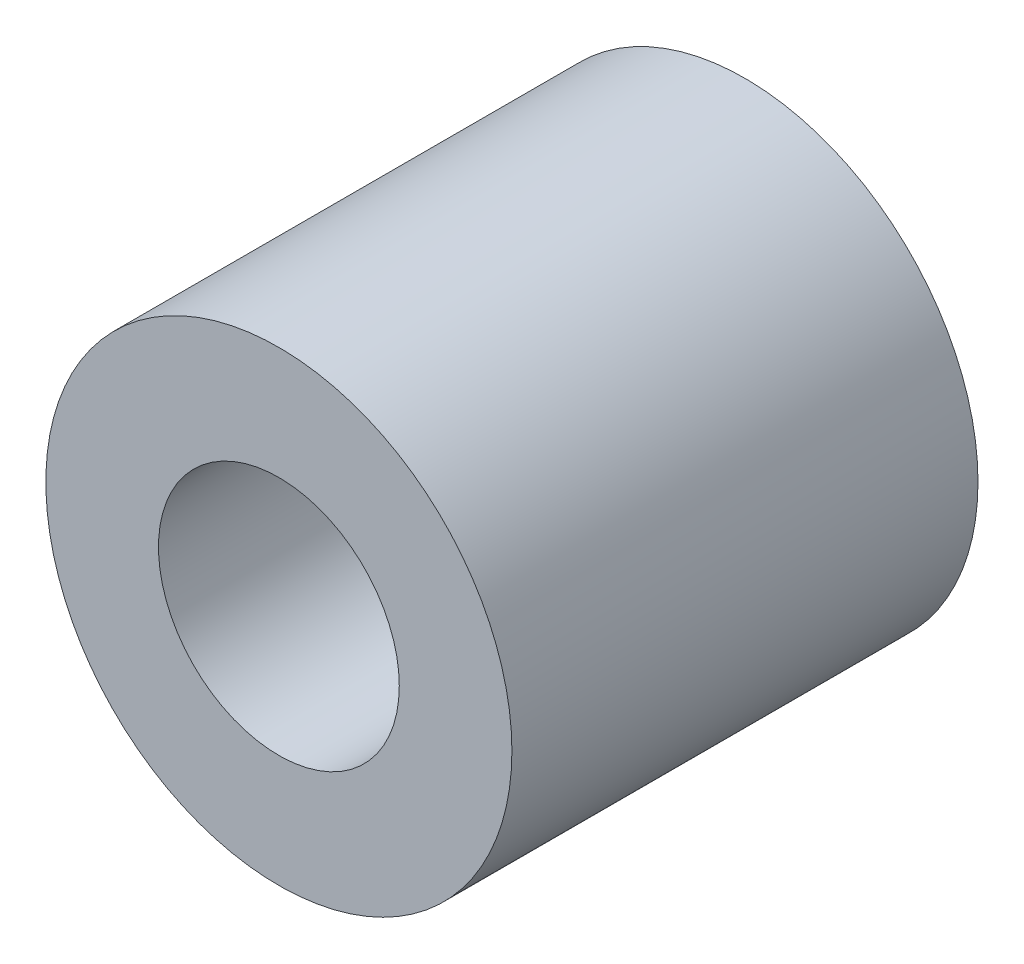
SolidWorks part; units mm, degrees
material "ABS"
ref_plane "Plan de face" through (0, 0, 0) normal (0, 0, 1) x (1, 0, 0)
ref_plane "Plan de dessus" through (0, 0, 0) normal (0, 1, 0) x (1, 0, 0)
ref_plane "Plan de droite" through (0, 0, 0) normal (1, 0, 0) x (0, 0, -1)
sketch "Esquisse1" plane through (0, 0, 0) normal (0, 0, 1) x (1, 0, 0)
  circle A0 centre (0, 0) radius 3
  dimension "D1" = 6
extrude "Boss.-Extru.1" add sketch "Esquisse1" along normal blind 6
sketch "Esquisse2" plane through (0, 0, 6) normal (0, 0, 1) x (1, 0, 0)
  circle A0 centre (0, 0) radius 1.55
  dimension "D1" = 3.1
extrude "Enlèv. mat.-Extru.1" cut sketch "Esquisse2" against normal through all
